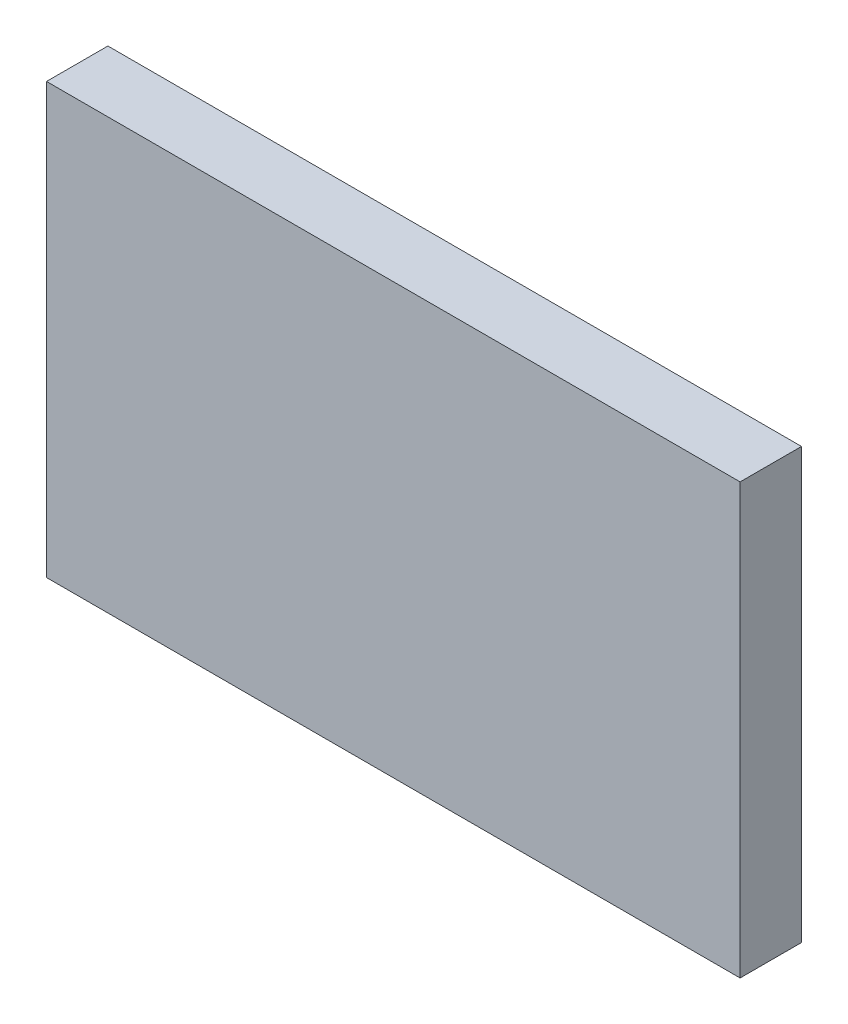
SolidWorks part; units mm, degrees
material "PE High Density"
ref_plane "Front Plane" through (0, 0, 0) normal (0, 0, 1) x (1, 0, 0)
ref_plane "Top Plane" through (0, 0, 0) normal (0, 1, 0) x (1, 0, 0)
ref_plane "Right Plane" through (0, 0, 0) normal (1, 0, 0) x (0, 0, -1)
sketch "Sketch1" plane through (0, 0, 0) normal (0, 0, 1) x (1, 0, 0)
  line L0 (-35.8775, 0) -> (35.8775, 0)
  line L1 (35.8775, 0) -> (35.8775, 44.45)
  line L2 (35.8775, 44.45) -> (-35.8775, 44.45)
  line L3 (-35.8775, 44.45) -> (-35.8775, 0)
  point P4 (0, 0)
  dimension "D1" = 44.45
  dimension "D2" = 71.755
extrude "Boss-Extrude1" add sketch "Sketch1" along normal mid plane 6.35
